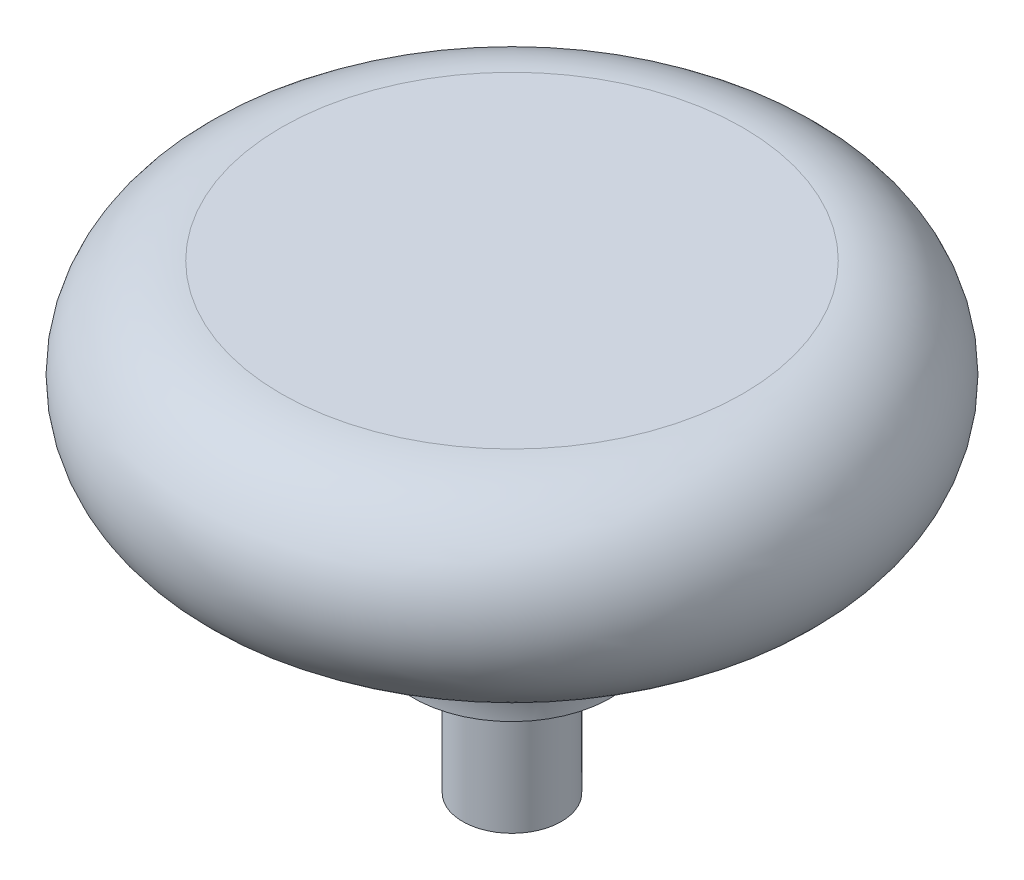
SolidWorks part; units mm, degrees
ref_plane "Front Plane" through (0, 0, 0) normal (0, 0, 1) x (1, 0, 0)
ref_plane "Top Plane" through (0, 0, 0) normal (0, 1, 0) x (1, 0, 0)
ref_plane "Right Plane" through (0, 0, 0) normal (1, 0, 0) x (0, 0, -1)
sketch "Sketch1" plane through (0, 0, 0) normal (0, 0, 1) x (1, 0, 0)
  line L0 (0, 0) -> (0, 8514.6824) construction
  line L1 (0, 0) -> (-8514.6824, 0) construction
  line L2 (-11.12, 0) -> (11.12, 0) construction
  line L3 (0, 4.76) -> (11.12, 4.76)
  line L4 (9.4499, -4.9822) -> (11.1179, -4.76)
  line L5 (4.765, -11.11) -> (2.38, -11.11)
  line L6 (2.38, -11.11) -> (2.38, -17.46)
  line L7 (2.38, -17.46) -> (0, -17.46)
  line L8 (0, -17.46) -> (0, 4.76)
  arc A1 (11.1179, -4.76) -> (11.12, 4.76) centre (11.12, 0) ccw
  arc A2 (9.4499, -4.9822) -> (4.765, -11.11) centre (11.115, -11.11) ccw
  point P7 (0, 0)
  point P8 (0, 0)
  point P11 (11.1129, -4.76)
  point P17 (0, 0)
  point P20 (11.12, -4.7531)
  point P21 (10.9404, -4.7566)
  point P22 (9.4499, -4.9822)
  dimension "D2" = 4.76
  dimension "D3" = 6.35
  dimension "D1" = 11.12
  dimension "D4" = 6.35
  dimension "D5" = 2.38
  dimension "D6" = 22.22
  dimension "D7" = 11.12
  dimension "D8" = 2.385
revolve "Revolve2" add sketch "Sketch1" angle 360 about L0
